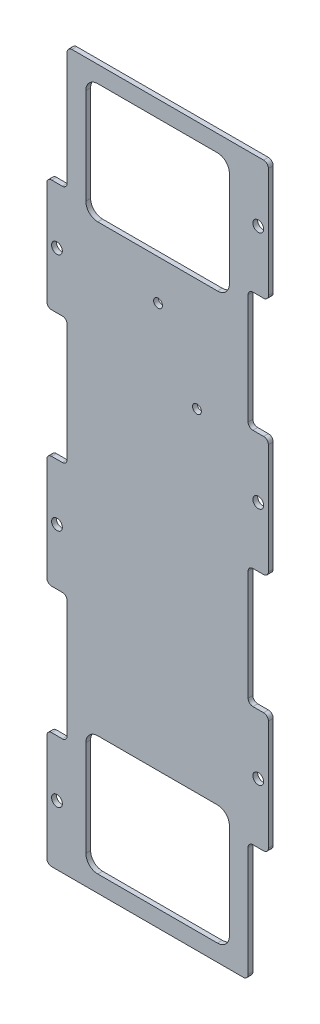
SolidWorks part; units mm, degrees
material "Acrylic (Medium-high impact)"
ref_plane "Front Plane" through (0, 0, 0) normal (0, 0, 1) x (1, 0, 0)
ref_plane "Top Plane" through (0, 0, 0) normal (0, 1, 0) x (1, 0, 0)
ref_plane "Right Plane" through (0, 0, 0) normal (1, 0, 0) x (0, 0, -1)
sketch "Sketch1" plane through (0, 0, 0) normal (0, 0, 1) x (1, 0, 0)
  line L1 (46.3, -150) -> (-46.3, -150)
  line L2 (46.3, -150) -> (46.3, 150)
  line L3 (46.3, 150) -> (-46.3, 150)
  line L4 (-46.3, -150) -> (-46.3, 150)
  line L5 (46.3, -150) -> (-46.3, 150) construction
  line L6 (46.3, 150) -> (-46.3, -150) construction
  point P0 (0, 0)
  dimension "D1" = 92.6
  dimension "D2" = 300
extrude "Boss-Extrude1" add sketch "Sketch1" along normal blind 2
sketch "Sketch2" plane through (0, 0, 0) normal (0, 0, 1) x (1, 0, 0)
  line L0 (-42.06, 150.5) -> (-42.06, -149.5) construction
  line L1 (42.06, 150.5) -> (42.06, -149.5) construction
  line L82 (-37.82, 98.5) -> (-46.3, 98.5)
  line L91 (-37.82, 98.5) -> (-37.82, 150)
  line L104 (-37.82, 150) -> (-46.3, 150)
  line L109 (-46.3, 98.5) -> (-46.3, 150)
  line L112 (-46.3, -150) -> (46.3, -150) construction
  line L115 (-37.82, 98.5) -> (-46.3, 150) construction
  line L116 (-37.82, 150) -> (-46.3, 98.5) construction
  line L121 (37.82, 100) -> (46.3, 100)
  line L122 (37.82, 100) -> (37.82, 50)
  line L127 (37.82, 50) -> (46.3, 50)
  line L128 (46.3, 100) -> (46.3, 50)
  line L133 (37.82, 100) -> (46.3, 50) construction
  line L134 (37.82, 50) -> (46.3, 100) construction
  line L135 (46.3, -50) -> (37.82, -50)
  line L136 (46.3, -50) -> (46.3, 0)
  line L137 (46.3, 0) -> (37.82, 0)
  line L138 (37.82, -50) -> (37.82, 0)
  line L139 (46.3, -50) -> (37.82, 0) construction
  line L140 (46.3, 0) -> (37.82, -50) construction
  line L141 (-37.82, -1.5) -> (-46.3, -1.5)
  line L142 (-37.82, -1.5) -> (-37.82, 51.5)
  line L143 (-37.82, 51.5) -> (-46.3, 51.5)
  line L144 (-46.3, -1.5) -> (-46.3, 51.5)
  line L145 (-37.82, -1.5) -> (-46.3, 51.5) construction
  line L146 (-37.82, 51.5) -> (-46.3, -1.5) construction
  line L147 (-37.82, -101.5) -> (-46.3, -101.5)
  line L148 (-37.82, -101.5) -> (-37.82, -48.5)
  line L149 (-37.82, -48.5) -> (-46.3, -48.5)
  line L150 (-46.3, -101.5) -> (-46.3, -48.5)
  line L151 (-37.82, -101.5) -> (-46.3, -48.5) construction
  line L152 (-37.82, -48.5) -> (-46.3, -101.5) construction
  line L153 (37.82, -150) -> (46.3, -150)
  line L154 (37.82, -150) -> (37.82, -100)
  line L155 (37.82, -100) -> (46.3, -100)
  line L156 (46.3, -150) -> (46.3, -100)
  line L157 (37.82, -150) -> (46.3, -100) construction
  line L158 (37.82, -100) -> (46.3, -150) construction
  line L159 (42.06, 50) -> (-134.3061, 50) construction
  line L160 (46.3, 150) -> (-46.3, 150) construction
  circle A30 centre (-42.06, 75) radius 2.25
  circle A31 centre (42.06, 125) radius 2.25
  circle A32 centre (42.06, 25) radius 2.25
  circle A33 centre (42.06, -75) radius 2.25
  circle A34 centre (-42.06, -25) radius 2.25
  circle A35 centre (-42.06, -125) radius 2.25
  point P8 (-42.06, 124.25)
  point P10 (-42.06, 25)
  point P19 (42.06, 75)
  point P24 (-42.06, -75)
  point P32 (42.06, -25)
  point P39 (42.06, -125)
  dimension "D4" = 84.12
  dimension "D5" = 8.48
  dimension "D15" = 75
  dimension "D17" = 53
  dimension "D23" = 8.48
  dimension "D26" = 0
  dimension "D1" = 4.5
  dimension "D2" = 4.5
  dimension "D12" = 4.5
  dimension "D14" = 4.5
  dimension "D20" = 4.5
  dimension "D22" = 4.5
  dimension "D3" = 25
  dimension "D6" = 51.5
  dimension "D7" = 8.48
  dimension "D8" = 50
  dimension "D9" = 50
  dimension "D10" = 8.48
  dimension "D11" = 75
  dimension "D13" = 100
  dimension "D16" = 53
  dimension "D18" = 8.48
  dimension "D19" = 125
  dimension "D21" = 50
  dimension "D24" = 100
  dimension "D25" = 42.06
  dimension "D27" = 75
  dimension "D28" = 75
  dimension "D29" = 25
  dimension "D30" = 0
  dimension "D31" = 125
extrude "Cut-Extrude1" cut sketch "Sketch2" along normal blind 10
fillet "Fillet1" radius 2 24 edges at (-46.3, 51.5, 1) (-37.82, 51.5, 1) (-37.82, -1.5, 1) (-46.3, -1.5, 1) (-46.3, -48.5, 1) (-37.82, -48.5, 1) (-37.82, -101.5, 1) (-46.3, -101.5, 1) (-46.3, -150, 1) (37.82, -150, 1) (37.82, -100, 1) (46.3, -100, 1) (46.3, -50, 1) (37.82, -50, 1) (37.82, 0, 1) (46.3, 0, 1) (46.3, 50, 1) (37.82, 50, 1) (37.82, 100, 1) (46.3, 100, 1) (46.3, 150, 1) (-37.82, 150, 1) (-37.82, 98.5, 1) (-46.3, 98.5, 1)
sketch "Sketch4" plane through (0, 0, 0) normal (0, 0, -1) x (-1, 0, 0)
  line L0 (0, -150) -> (0, 248.5698) construction
  line L1 (-42, 148) -> (42, 148) construction
  line L2 (25, 93) -> (-25, 93)
  line L3 (30, 98) -> (30, 138)
  line L4 (25, 143) -> (-25, 143)
  line L5 (-30, 98) -> (-30, 138)
  line L6 (30, 93) -> (-30, 143) construction
  line L7 (30, 143) -> (-30, 93) construction
  line L9 (25, -143) -> (-25, -143)
  line L10 (30, -138) -> (30, -98)
  line L11 (25, -93) -> (-25, -93)
  line L12 (-30, -138) -> (-30, -98)
  line L13 (30, -143) -> (-30, -93) construction
  line L14 (30, -93) -> (-30, -143) construction
  line L16 (44.3, -150) -> (-35.82, -150) construction
  arc A0 (30, -98) -> (25, -93) centre (25, -98) ccw
  arc A1 (25, -143) -> (30, -138) centre (25, -138) ccw
  arc A2 (-25, -143) -> (-30, -138) centre (-25, -138) cw
  arc A3 (-25, -93) -> (-30, -98) centre (-25, -98) ccw
  arc A4 (25, 93) -> (30, 98) centre (25, 98) ccw
  arc A5 (-25, 93) -> (-30, 98) centre (-25, 98) cw
  arc A6 (-25, 143) -> (-30, 138) centre (-25, 138) ccw
  arc A7 (30, 138) -> (25, 143) centre (25, 138) ccw
  point P4 (0, 118)
  point P12 (0, -116.8)
  dimension "D7" = 5
  dimension "D1" = 60
  dimension "D2" = 50
  dimension "D3" = 7
  dimension "D4" = 60
  dimension "D5" = 50
  dimension "D6" = 5
extrude "Cut-Extrude3" cut sketch "Sketch4" against normal blind 8.5
sketch "Sketch5" plane through (0, 0, 0) normal (0, 0, -1) x (-1, 0, 0)
  circle A0 centre (-16.43, 46) radius 1.85
  circle A1 centre (-0.18, 76.2) radius 1.85
  dimension "D1" = 3.7
  dimension "D2" = 3.7
extrude "Cut-Extrude4" cut sketch "Sketch5" against normal blind 10
